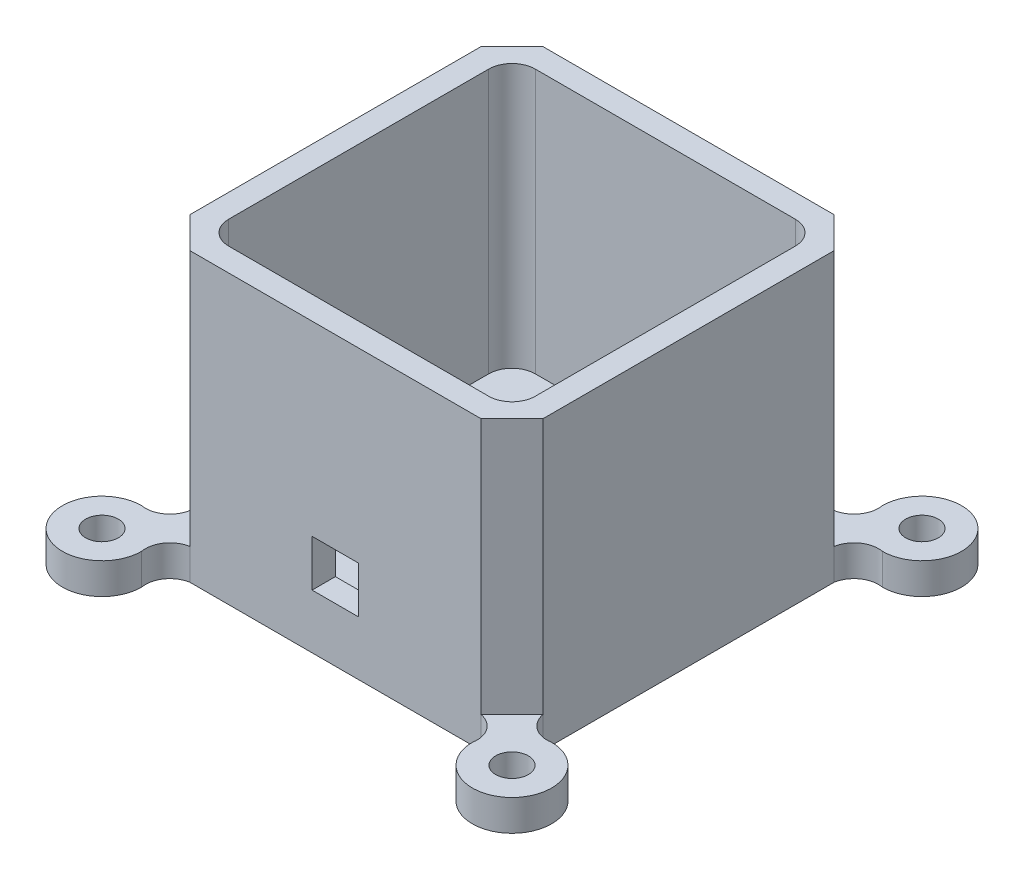
SolidWorks part; units mm, degrees
ref_plane "Piano frontale" through (0, 0, 0) normal (0, 0, 1) x (1, 0, 0)
ref_plane "Piano superiore" through (0, 0, 0) normal (0, 1, 0) x (1, 0, 0)
ref_plane "Piano destro" through (0, 0, 0) normal (1, 0, 0) x (0, 0, -1)
sketch "Schizzo1" plane through (0, 0, 0) normal (0, 1, 0) x (1, 0, 0)
  line L0 (-18.75, 22.75) -> (18.75, 22.75)
  line L1 (-16.75, 19.75) -> (16.75, 19.75)
  line L2 (-19.75, 16.75) -> (-19.75, -16.75)
  line L3 (-16.75, -19.75) -> (16.75, -19.75)
  line L4 (19.75, 16.75) -> (19.75, -16.75)
  line L5 (22.75, 18.75) -> (22.75, -18.75)
  line L6 (-18.75, -22.75) -> (18.75, -22.75)
  line L7 (-22.75, 18.75) -> (-22.75, -18.75)
  line L8 (-19.75, 19.75) -> (-19.75, -19.75) construction
  line L9 (-19.75, -19.75) -> (19.75, -19.75) construction
  line L10 (19.75, 19.75) -> (19.75, -19.75) construction
  line L11 (-19.75, 19.75) -> (19.75, 19.75) construction
  line L12 (-22.75, 22.75) -> (22.75, 22.75) construction
  line L13 (-22.75, 22.75) -> (-22.75, -22.75) construction
  line L14 (-22.75, 18.75) -> (-18.75, 22.75)
  line L15 (22.75, 22.75) -> (22.75, -22.75) construction
  line L16 (18.75, 22.75) -> (22.75, 18.75)
  line L17 (-22.75, -22.75) -> (22.75, -22.75) construction
  line L18 (22.75, -18.75) -> (18.75, -22.75)
  line L19 (-22.75, -18.75) -> (-18.75, -22.75)
  arc A0 (-19.75, -16.75) -> (-16.75, -19.75) centre (-16.75, -16.75) ccw
  arc A1 (16.75, -19.75) -> (19.75, -16.75) centre (16.75, -16.75) ccw
  arc A2 (16.75, 19.75) -> (19.75, 16.75) centre (16.75, 16.75) cw
  arc A3 (-16.75, 19.75) -> (-19.75, 16.75) centre (-16.75, 16.75) ccw
  point P11 (-19.75, -19.75)
  dimension "D4" = 3
  dimension "D3" = 3
extrude "Estrusione-Estrusione3" add sketch "Schizzo1" along normal blind 37
sketch "Schizzo5" plane through (0, 0, 0) normal (0, 1, 0) x (1, 0, 0)
  line L0 (-18.75, 22.75) -> (-22.75, 18.75) construction
  line L1 (-22.75, 18.75) -> (-18.75, 22.75)
  line L2 (18.75, 22.75) -> (22.75, 18.75)
  line L3 (22.75, -18.75) -> (18.75, -22.75)
  line L4 (-18.75, -22.75) -> (-22.75, -18.75)
  circle A0 centre (-26.4069, 26.4069) radius 2.1
  arc A1 (-21.3069, 26.4069) -> (-26.4069, 21.3069) centre (-26.4069, 26.4069) ccw
  arc A2 (-22.75, 18.75) -> (-26.4069, 21.3069) centre (-25.8569, 18.2) ccw
  arc A3 (-18.75, 22.75) -> (-21.3069, 26.4069) centre (-18.2, 25.8569) cw
  arc A4 (18.75, 22.75) -> (21.3069, 26.4069) centre (18.2, 25.8569) ccw
  arc A5 (26.4069, 21.3069) -> (21.3069, 26.4069) centre (26.4069, 26.4069) ccw
  circle A6 centre (26.4069, 26.4069) radius 2.1
  arc A7 (22.75, 18.75) -> (26.4069, 21.3069) centre (25.8569, 18.2) cw
  arc A8 (22.75, -18.75) -> (26.4069, -21.3069) centre (25.8569, -18.2) ccw
  arc A9 (21.3069, -26.4069) -> (26.4069, -21.3069) centre (26.4069, -26.4069) ccw
  circle A10 centre (26.4069, -26.4069) radius 2.1
  arc A11 (18.75, -22.75) -> (21.3069, -26.4069) centre (18.2, -25.8569) cw
  arc A12 (-18.75, -22.75) -> (-21.3069, -26.4069) centre (-18.2, -25.8569) ccw
  arc A13 (-26.4069, -21.3069) -> (-21.3069, -26.4069) centre (-26.4069, -26.4069) ccw
  circle A14 centre (-26.4069, -26.4069) radius 2.1
  arc A15 (-22.75, -18.75) -> (-26.4069, -21.3069) centre (-25.8569, -18.2) cw
  circle A16 centre (-26.4069, 26.4069) radius 5.1 construction
  point P4 (-20.75, 20.75)
  point P43 (0, 0)
  point P50 (0, 0)
  dimension "D2" = 3
  dimension "D1" = 4.2
  dimension "D3" = 8
  dimension "D4" = 4
sketch "Schizzo6" plane through (0, 0, 0) normal (0, 1, 0) x (1, 0, 0)
  line L0 (-18.75, 22.75) -> (-22.75, 18.75) construction
  line L1 (-22.75, 18.75) -> (-22.75, -18.75) construction
  line L2 (18.75, 22.75) -> (-18.75, 22.75) construction
  line L3 (22.75, 18.75) -> (18.75, 22.75) construction
  line L4 (22.75, -18.75) -> (22.75, 18.75) construction
  line L5 (18.75, -22.75) -> (22.75, -18.75) construction
  line L6 (-18.75, -22.75) -> (18.75, -22.75) construction
  line L7 (-22.75, -18.75) -> (-18.75, -22.75) construction
  line L8 (-18.75, 22.75) -> (-22.75, 18.75)
  line L9 (-22.75, 18.75) -> (-22.75, -18.75)
  line L10 (18.75, 22.75) -> (-18.75, 22.75)
  line L11 (22.75, 18.75) -> (18.75, 22.75)
  line L12 (22.75, -18.75) -> (22.75, 18.75)
  line L13 (18.75, -22.75) -> (22.75, -18.75)
  line L14 (-18.75, -22.75) -> (18.75, -22.75)
  line L15 (-22.75, -18.75) -> (-18.75, -22.75)
extrude "Estrusione-Estrusione6" add sketch "Schizzo6" along normal blind 3
extrude "Estrusione-Estrusione5" add sketch "Schizzo5" along normal blind 4
sketch "Schizzo7" plane through (0, 0, 22.75) normal (0, 0, 1) x (1, 0, 0)
  line L1 (-3, 13) -> (3, 13)
  line L2 (-3, 13) -> (-3, 7)
  line L3 (-3, 7) -> (3, 7)
  line L4 (3, 13) -> (3, 7)
  dimension "D1" = 6
  dimension "D2" = 6
extrude "Taglio-Estrusione1" cut sketch "Schizzo7" against normal blind 3
